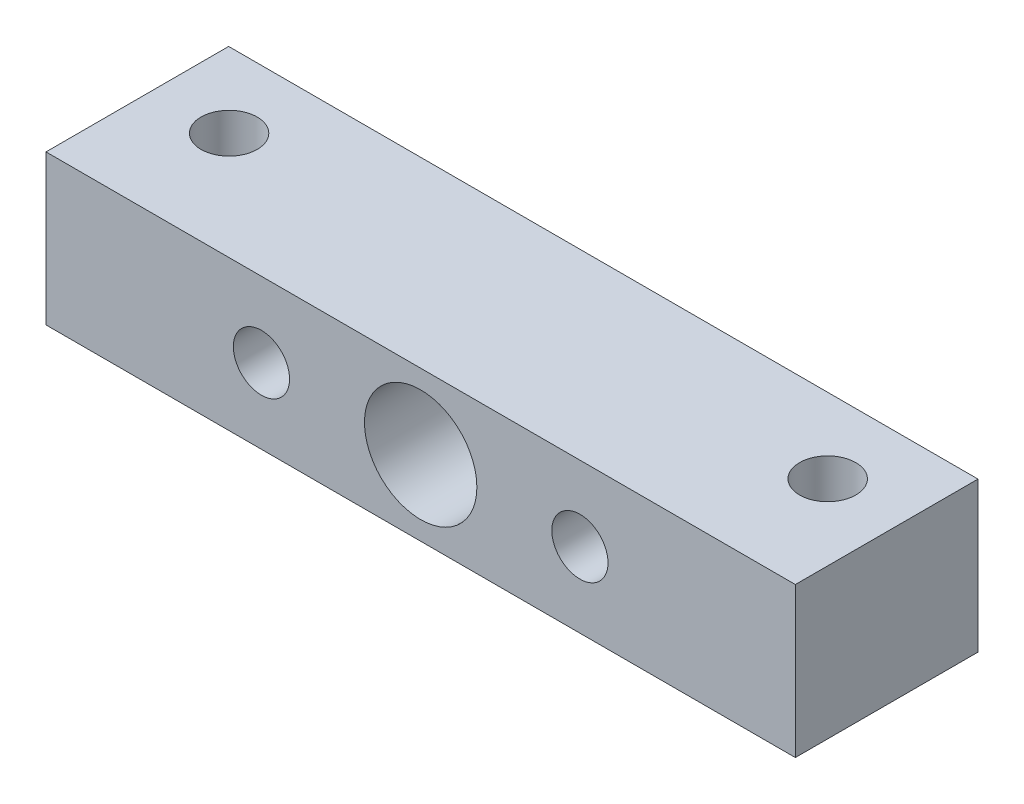
SolidWorks part; units mm, degrees
ref_plane "Front" through (0, 0, 0) normal (0, 0, 1) x (1, 0, 0)
ref_plane "Top" through (0, 0, 0) normal (0, 1, 0) x (1, 0, 0)
ref_plane "Right" through (0, 0, 0) normal (1, 0, 0) x (0, 0, -1)
sketch "Sketch1" plane through (0, 0, 0) normal (0, 1, 0) x (1, 0, 0)
  line L0 (-20, 0) -> (20, 0) construction
  line L1 (20, -4.875) -> (-20, -4.875)
  line L2 (20, -4.875) -> (20, 4.875)
  line L3 (20, 4.875) -> (-20, 4.875)
  line L4 (-20, -4.875) -> (-20, 4.875)
  line L5 (20, -4.875) -> (-20, 4.875) construction
  line L6 (20, 4.875) -> (-20, -4.875) construction
  line L7 (0, 4.875) -> (0, -4.875) construction
  circle A0 centre (-15.9761, 0.875) radius 1.5
  circle A1 centre (15.9761, 0.875) radius 1.5
  point P0 (0, 0)
  dimension "D3" = 3
  dimension "D1" = 40
  dimension "D2" = 9.75
  dimension "D4" = 16
  dimension "D5" = 4
extrude "Boss-Extrude1" add sketch "Sketch1" along normal blind 8
sketch "Sketch2" plane through (0, 0, 4.875) normal (0, 0, 1) x (1, 0, 0)
  line L0 (0, 8) -> (0, 0) construction
  line L1 (-20, 8) -> (20, 8) construction
  line L2 (-20, 0) -> (20, 0) construction
  line L3 (20, 8) -> (20, 0) construction
  circle A0 centre (0, 4) radius 3
  circle A1 centre (8.5, 4) radius 1.5
  circle A2 centre (-8.5, 4) radius 1.5
  point P10 (20, 4)
  dimension "D1" = 6
  dimension "D3" = 3
  dimension "D2" = 11.5
extrude "Cut-Extrude1" cut sketch "Sketch2" against normal up to next
